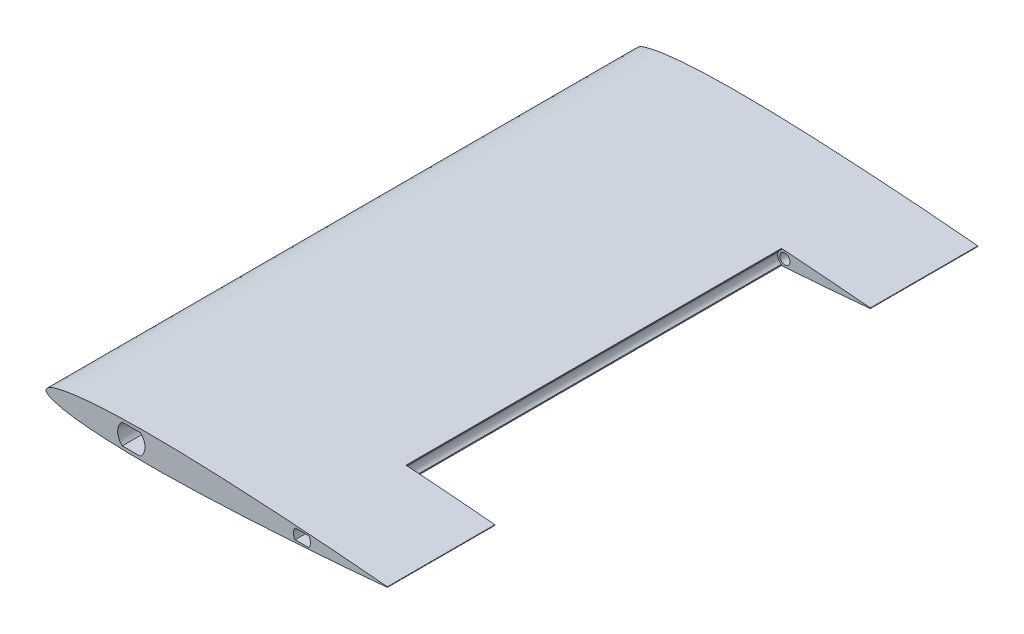
SolidWorks part; units mm, degrees
material "Foam"
ref_plane "Piano frontale" through (0, 0, 0) normal (0, 0, 1) x (1, 0, 0)
ref_plane "Piano superiore" through (0, 0, 0) normal (0, 1, 0) x (1, 0, 0)
ref_plane "Piano destro" through (0, 0, 0) normal (1, 0, 0) x (0, 0, -1)
curve "ProfiloBase"
  spline degree 3 poles (100, 0.084, 0) (98.3335, 0.2367, 0) (95.0012, 0.5422, 0) (88.3356, 1.1109, 0) (80.0033, 1.7636, 0) (70.003, 2.4579, 0) (60.0031, 3.0617, 0) (50.003, 3.5521, 0) (40.0026, 3.9029, 0) (31.667, 4.0253, 0) (24.9992, 3.9769, 0) (19.9978, 3.845, 0) (14.9934, 3.5925, 0) (10.8272, 3.2377, 0) (7.4891, 2.814, 0) (4.9936, 2.4037, 0) (2.8496, 1.8679, 0) (1.1654, 1.321, 0) (-0.6646, 0, 0) (1.1654, -1.321, 0) (2.8496, -1.8679, 0) (4.9936, -2.4037, 0) (7.4891, -2.814, 0) (10.8272, -3.2377, 0) (14.9934, -3.5925, 0) (19.9978, -3.845, 0) (24.9992, -3.9769, 0) (31.667, -4.0253, 0) (40.0026, -3.9029, 0) (50.003, -3.5521, 0) (60.0031, -3.0617, 0) (70.003, -2.4579, 0) (80.0033, -1.7636, 0) (88.3356, -1.1109, 0) (95.0012, -0.5422, 0) (98.3335, -0.2367, 0) (100, -0.084, 0) knots 0 0 0 0 0.024876 0.049742 0.099443 0.149112 0.198751 0.248359 0.297937 0.347491 0.372267 0.397051 0.421859 0.446731 0.45922 0.471791 0.48456 0.491195 0.5 0.508805 0.51544 0.528209 0.54078 0.553269 0.578141 0.602949 0.627733 0.652509 0.702063 0.751641 0.801249 0.850888 0.900557 0.950258 0.975124 1 1 1 1
sketch "Schizzo1" plane through (0, 0, 0) normal (0, 0, 1) x (1, 0, 0)
  line L0 (100, 0.084) -> (100, -0.084) construction
  arc A0 (100, 0.084) -> (100, -0.084) centre (100, 0) cw
  spline S0 degree 3 poles (1265.2106, 6875.158) (458.4991, -96.3936) (277.9953, -15.0713) (88.3356, 1.1109) (80.0033, 1.7636) (70.003, 2.4579) (60.0031, 3.0617) (50.003, 3.5521) (40.0026, 3.9029) (31.667, 4.0253) (24.9992, 3.9769) (19.9978, 3.845) (14.9934, 3.5925) (10.8272, 3.2377) (7.4891, 2.814) (4.9936, 2.4037) (2.8496, 1.8679) (1.1654, 1.321) (-0.6646, 0) (1.1654, -1.321) (2.8496, -1.8679) (4.9936, -2.4037) (7.4891, -2.814) (10.8272, -3.2377) (14.9934, -3.5925) (19.9978, -3.845) (24.9992, -3.9769) (31.667, -4.0253) (40.0026, -3.9029) (50.003, -3.5521) (60.0031, -3.0617) (70.003, -2.4579) (80.0033, -1.7636) (88.3356, -1.1109) (277.9935, 15.0711) (458.4956, 96.392) (1265.1864, -6874.9491) knots -2.730056 -2.730056 -2.730056 -2.730056 0.024876 0.049742 0.099443 0.149112 0.198751 0.248359 0.297937 0.347491 0.372267 0.397051 0.421859 0.446731 0.45922 0.471791 0.48456 0.491195 0.5 0.508805 0.51544 0.528209 0.54078 0.553269 0.578141 0.602949 0.627733 0.652509 0.702063 0.751641 0.801249 0.850888 0.900557 0.950258 0.975124 3.730029 3.730029 3.730029 3.730029 only from (100, 0.084) to (100, -0.084) construction
  spline S1 degree 3 poles (100, 0.084) (98.3335, 0.2367) (95.0012, 0.5422) (88.3356, 1.1109) (80.0033, 1.7636) (70.003, 2.4579) (60.0031, 3.0617) (50.003, 3.5521) (40.0026, 3.9029) (31.667, 4.0253) (24.9992, 3.9769) (19.9978, 3.845) (14.9934, 3.5925) (10.8272, 3.2377) (7.4891, 2.814) (4.9936, 2.4037) (2.8496, 1.8679) (1.1654, 1.321) (-0.6646, 0) (1.1654, -1.321) (2.8496, -1.8679) (4.9936, -2.4037) (7.4891, -2.814) (10.8272, -3.2377) (14.9934, -3.5925) (19.9978, -3.845) (24.9992, -3.9769) (31.667, -4.0253) (40.0026, -3.9029) (50.003, -3.5521) (60.0031, -3.0617) (70.003, -2.4579) (80.0033, -1.7636) (88.3356, -1.1109) (95.0012, -0.5422) (98.3335, -0.2367) (100, -0.084) knots 0 0 0 0 0.024876 0.049742 0.099443 0.149112 0.198751 0.248359 0.297937 0.347491 0.372267 0.397051 0.421859 0.446731 0.45922 0.471791 0.48456 0.491195 0.5 0.508805 0.51544 0.528209 0.54078 0.553269 0.578141 0.602949 0.627733 0.652509 0.702063 0.751641 0.801249 0.850888 0.900557 0.950258 0.975124 1 1 1 1
  point P5 (100, 0)
extrude "FoamAlta" add sketch "Schizzo1" along normal blind 31.5
sketch "Schizzo2" plane through (0, 0, 31.5) normal (0, 0, 1) x (1, 0, 0)
  line L0 (75, 2.1072) -> (75, -2.1072) construction
  arc A4 (75, 2.1072) -> (75, -2.1072) centre (75, 0) ccw
  spline S1 degree 3 poles (633.0503, 1915.9881) (335.6221, -48.8321) (214.9188, -9.6895) (88.3356, 1.1109) (80.0033, 1.7636) (70.003, 2.4579) (60.0031, 3.0617) (50.003, 3.5521) (40.0026, 3.9029) (31.667, 4.0253) (24.9992, 3.9769) (19.9978, 3.845) (14.9934, 3.5925) (10.8272, 3.2377) (7.4891, 2.814) (4.9936, 2.4037) (2.8496, 1.8679) (1.1654, 1.321) (-0.6646, 0) (1.1654, -1.321) (2.8496, -1.8679) (4.9936, -2.4037) (7.4891, -2.814) (10.8272, -3.2377) (14.9934, -3.5925) (19.9978, -3.845) (24.9992, -3.9769) (31.667, -4.0253) (40.0026, -3.9029) (50.003, -3.5521) (60.0031, -3.0617) (70.003, -2.4579) (80.0033, -1.7636) (88.3356, -1.1109) (214.9185, 9.6894) (335.6215, 48.8319) (633.0478, -1915.9718) knots -1.78903 -1.78903 -1.78903 -1.78903 0.024876 0.049742 0.099443 0.149112 0.198751 0.248359 0.297937 0.347491 0.372267 0.397051 0.421859 0.446731 0.45922 0.471791 0.48456 0.491195 0.5 0.508805 0.51544 0.528209 0.54078 0.553269 0.578141 0.602949 0.627733 0.652509 0.702063 0.751641 0.801249 0.850888 0.900557 0.950258 0.975124 2.789025 2.789025 2.789025 2.789025 only from (100, 0.084) to (100, -0.084) construction
  spline S2 degree 3 poles (75, 2.1072) (73.3336, 2.2229) (68.3351, 2.5586) (60.0031, 3.0617) (50.003, 3.5521) (40.0026, 3.9029) (31.667, 4.0253) (24.9992, 3.9769) (19.9978, 3.845) (14.9934, 3.5925) (10.8272, 3.2377) (7.4891, 2.814) (4.9936, 2.4037) (2.8496, 1.8679) (1.1654, 1.321) (-0.6646, 0) (1.1654, -1.321) (2.8496, -1.8679) (4.9936, -2.4037) (7.4891, -2.814) (10.8272, -3.2377) (14.9934, -3.5925) (19.9978, -3.845) (24.9992, -3.9769) (31.667, -4.0253) (40.0026, -3.9029) (50.003, -3.5521) (60.0031, -3.0617) (68.3351, -2.5586) (73.3336, -2.2229) (75, -2.1072) knots 0.124282 0.124282 0.124282 0.124282 0.149112 0.198751 0.248359 0.297937 0.347491 0.372267 0.397051 0.421859 0.446731 0.45922 0.471791 0.48456 0.491195 0.5 0.508805 0.51544 0.528209 0.54078 0.553269 0.578141 0.602949 0.627733 0.652509 0.702063 0.751641 0.801249 0.850888 0.875718 0.875718 0.875718 0.875718
  dimension "D1" = 4.2144
extrude "FoamMedia" add sketch "Schizzo2" along normal blind 110
sketch "Schizzo4" plane through (0, 0, 141.5) normal (0, 0, 1) x (1, 0, 0)
  line L1 (75, 2.1762) -> (74, 2.1762)
  line L2 (75, 2.1762) -> (75, -2.1762)
  line L3 (75, -2.1762) -> (74, -2.1762)
  line L4 (74, 2.1762) -> (74, -2.1762)
  spline S0 degree 3 poles (75, 2.1072) (73.3336, 2.2229) (68.3351, 2.5586) (60.0031, 3.0617) (50.003, 3.5521) (40.0026, 3.9029) (31.667, 4.0253) (24.9992, 3.9769) (19.9978, 3.845) (14.9934, 3.5925) (10.8272, 3.2377) (7.4891, 2.814) (4.9936, 2.4037) (2.8496, 1.8679) (1.1654, 1.321) (-0.6646, 0) (1.1654, -1.321) (2.8496, -1.8679) (4.9936, -2.4037) (7.4891, -2.814) (10.8272, -3.2377) (14.9934, -3.5925) (19.9978, -3.845) (24.9992, -3.9769) (31.667, -4.0253) (40.0026, -3.9029) (50.003, -3.5521) (60.0031, -3.0617) (68.3351, -2.5586) (73.3336, -2.2229) (75, -2.1072) knots 0.124282 0.124282 0.124282 0.124282 0.149112 0.198751 0.248359 0.297937 0.347491 0.372267 0.397051 0.421859 0.446731 0.45922 0.471791 0.48456 0.491195 0.5 0.508805 0.51544 0.528209 0.54078 0.553269 0.578141 0.602949 0.627733 0.652509 0.702063 0.751641 0.801249 0.850888 0.875718 0.875718 0.875718 0.875718 construction
  dimension "D1" = 1
extrude "SmussoParteMobile" cut sketch "Schizzo4" against normal up to surface (110 mm away) up to face at (86.9942, -0.5058, 31.5)
sketch "Schizzo6" plane through (0, 0, 141.5) normal (0, 0, 1) x (1, 0, 0)
  arc A0 (100, 0.084) -> (100, -0.084) centre (100, 0) cw
  spline S0 degree 3 poles (774.5938, 2905.893) (370.1816, -60.6448) (232.5901, -11.1972) (88.3356, 1.1109) (80.0033, 1.7636) (70.003, 2.4579) (60.0031, 3.0617) (50.003, 3.5521) (40.0026, 3.9029) (31.667, 4.0253) (24.9992, 3.9769) (19.9978, 3.845) (14.9934, 3.5925) (10.8272, 3.2377) (7.4891, 2.814) (4.9936, 2.4037) (2.8496, 1.8679) (1.1654, 1.321) (-0.6646, 0) (1.1654, -1.321) (2.8496, -1.8679) (4.9936, -2.4037) (7.4891, -2.814) (10.8272, -3.2377) (14.9934, -3.5925) (19.9978, -3.845) (24.9992, -3.9769) (31.667, -4.0253) (40.0026, -3.9029) (50.003, -3.5521) (60.0031, -3.0617) (70.003, -2.4579) (80.0033, -1.7636) (88.3356, -1.1109) (232.5893, 11.1971) (370.1799, 60.6442) (774.5865, -2905.8392) knots -2.052665 -2.052665 -2.052665 -2.052665 0.024876 0.049742 0.099443 0.149112 0.198751 0.248359 0.297937 0.347491 0.372267 0.397051 0.421859 0.446731 0.45922 0.471791 0.48456 0.491195 0.5 0.508805 0.51544 0.528209 0.54078 0.553269 0.578141 0.602949 0.627733 0.652509 0.702063 0.751641 0.801249 0.850888 0.900557 0.950258 0.975124 3.052652 3.052652 3.052652 3.052652 only from (100, 0.084) to (100, -0.084) construction
  spline S1 degree 3 poles (100, 0.084) (98.3335, 0.2367) (95.0012, 0.5422) (88.3356, 1.1109) (80.0033, 1.7636) (70.003, 2.4579) (60.0031, 3.0617) (50.003, 3.5521) (40.0026, 3.9029) (31.667, 4.0253) (24.9992, 3.9769) (19.9978, 3.845) (14.9934, 3.5925) (10.8272, 3.2377) (7.4891, 2.814) (4.9936, 2.4037) (2.8496, 1.8679) (1.1654, 1.321) (-0.6646, 0) (1.1654, -1.321) (2.8496, -1.8679) (4.9936, -2.4037) (7.4891, -2.814) (10.8272, -3.2377) (14.9934, -3.5925) (19.9978, -3.845) (24.9992, -3.9769) (31.667, -4.0253) (40.0026, -3.9029) (50.003, -3.5521) (60.0031, -3.0617) (70.003, -2.4579) (80.0033, -1.7636) (88.3356, -1.1109) (95.0012, -0.5422) (98.3335, -0.2367) (100, -0.084) knots 0 0 0 0 0.024876 0.049742 0.099443 0.149112 0.198751 0.248359 0.297937 0.347491 0.372267 0.397051 0.421859 0.446731 0.45922 0.471791 0.48456 0.491195 0.5 0.508805 0.51544 0.528209 0.54078 0.553269 0.578141 0.602949 0.627733 0.652509 0.702063 0.751641 0.801249 0.850888 0.900557 0.950258 0.975124 1 1 1 1
extrude "FoamBassa" add sketch "Schizzo6" along normal blind 31.5
sketch "Schizzo5" plane through (0, 0, 31.5) normal (0, 0, 1) x (1, 0, 0)
  circle A0 centre (75, 0) radius 1.5
  dimension "D1" = 3
extrude "ForoPernoRuddevator" cut sketch "Schizzo5" against normal through all and the other way through all
sketch "Schizzo8" plane through (0, 0, 0) normal (0, 0, -1) x (-1, 0, 0)
  circle A0 centre (-25, 0) radius 3
  dimension "D1" = 6
  dimension "D2" = 25
extrude "ForoLongherone" cut sketch "Schizzo8" against normal through all
sketch "Schizzo9" plane through (0, 0, 0) normal (0, 0, -1) x (-1, 0, 0)
  line L1 (-27.6458, 3) -> (-22.3542, 3)
  line L3 (-27.6458, -3) -> (-22.3542, -3)
  arc A0 (-27.6458, 3) -> (-27.6458, -3) centre (-25, 0) ccw
  circle A1 centre (-25, 0) radius 3 construction
  arc A2 (-22.3542, -3) -> (-22.3542, 3) centre (-25, 0) ccw
  dimension "D1" = 8
extrude "AggancioLongheroneAlto" cut sketch "Schizzo9" against normal blind 15
sketch "Schizzo10" plane through (0, 0, 0) normal (0, 0, -1) x (-1, 0, 0)
  line L1 (-77, 1.5) -> (-73, 1.5)
  line L3 (-77, -1.5) -> (-73, -1.5)
  arc A0 (-77, 1.5) -> (-77, -1.5) centre (-75, 0) ccw
  circle A1 centre (-75, 0) radius 1.5 construction
  arc A2 (-73, -1.5) -> (-73, 1.5) centre (-75, 0) ccw
  dimension "D1" = 5
extrude "AggancioPernoAlto" cut sketch "Schizzo10" against normal blind 15
sketch "Schizzo11" plane through (0, 0, 173) normal (0, 0, 1) x (1, 0, 0)
  line L1 (22.3542, 3) -> (27.6458, 3)
  line L3 (22.3542, -3) -> (27.6458, -3)
  line L5 (73, 1.5) -> (77, 1.5)
  line L7 (73, -1.5) -> (77, -1.5)
  arc A0 (22.3542, 3) -> (22.3542, -3) centre (25, 0) ccw
  arc A1 (73, 1.5) -> (73, -1.5) centre (75, 0) ccw
  circle A2 centre (25, 0) radius 3 construction
  circle A3 centre (75, 0) radius 1.5 construction
  arc A4 (77, -1.5) -> (77, 1.5) centre (75, 0) ccw
  arc A5 (27.6458, -3) -> (27.6458, 3) centre (25, 0) ccw
  dimension "D1" = 8
  dimension "D2" = 5
extrude "AgganciLatoBasso" cut sketch "Schizzo11" against normal blind 15
